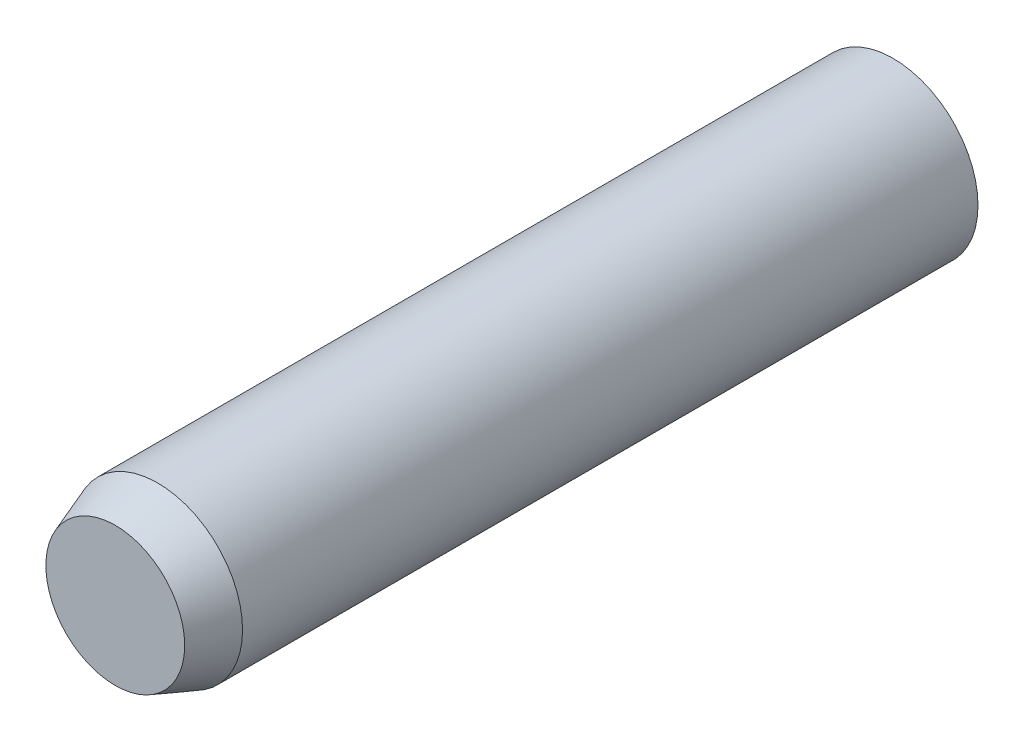
SolidWorks part; units mm, degrees
ref_plane "Front Plane" through (0, 0, 0) normal (0, 0, 1) x (1, 0, 0)
ref_plane "Top Plane" through (0, 0, 0) normal (0, 1, 0) x (1, 0, 0)
ref_plane "Right Plane" through (0, 0, 0) normal (1, 0, 0) x (0, 0, -1)
sketch "Sketch1" plane through (0, 0, 0) normal (0, 0, 1) x (1, 0, 0)
  circle A0 centre (0, 0) radius 6
  dimension "D1" = 12
extrude "Boss-Extrude1" add sketch "Sketch1" along normal blind 55
chamfer "Chamfer1" distance 3 angle 20 1 edges at (6, 0, 55)
